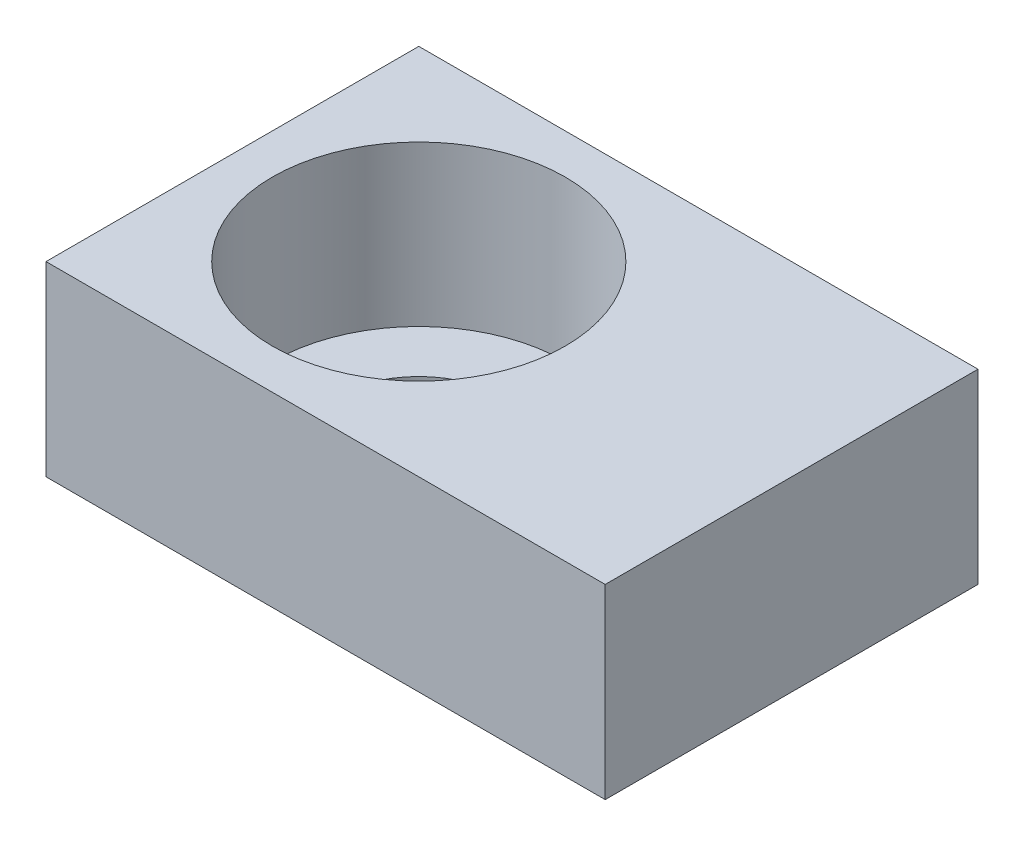
SolidWorks part; units mm, degrees
ref_plane "Alzado" through (0, 0, 0) normal (0, 0, 1) x (1, 0, 0)
ref_plane "Planta" through (0, 0, 0) normal (0, 1, 0) x (1, 0, 0)
ref_plane "Vista lateral" through (0, 0, 0) normal (1, 0, 0) x (0, 0, -1)
sketch "Croquis1" plane through (0, 0, 0) normal (0, 0, 1) x (1, 0, 0)
  line L0 (0, 0) -> (7, 0)
  line L3 (10.5, 0) -> (10.5, 3.5)
  line L4 (10.5, 3.5) -> (0, 3.5)
  line L5 (0, 3.5) -> (0, 0)
  line L6 (3.5, 0) -> (3.5, 3.5) construction
  line L7 (7, 0) -> (7, 0.5) construction
  line L8 (7, 0) -> (10.5, 0)
  dimension "D1" = 7
  dimension "D3" = 3.5
  dimension "D4" = 7
extrude "Saliente-Extruir1" add sketch "Croquis1" along normal blind 7
sketch "Croquis2" plane through (0, 0, 0) normal (0, -1, 0) x (1, 0, 0)
  line L0 (0, 7) -> (7, 0) construction
  line L1 (0, 7) -> (0, 0) construction
  line L2 (0, 0) -> (10.5, 0) construction
  circle A0 centre (3.5, 3.5) radius 1.6
  dimension "D1" = 3.2
  dimension "D2" = 7
extrude "Cortar-Extruir1" cut sketch "Croquis2" against normal blind 6
sketch "Croquis3" plane through (0, 3.5, 0) normal (0, 1, 0) x (1, 0, 0)
  circle A0 centre (3.5, -3.5) radius 2.75
  dimension "D1" = 5.5
extrude "Cortar-Extruir2" cut sketch "Croquis3" against normal blind 3
